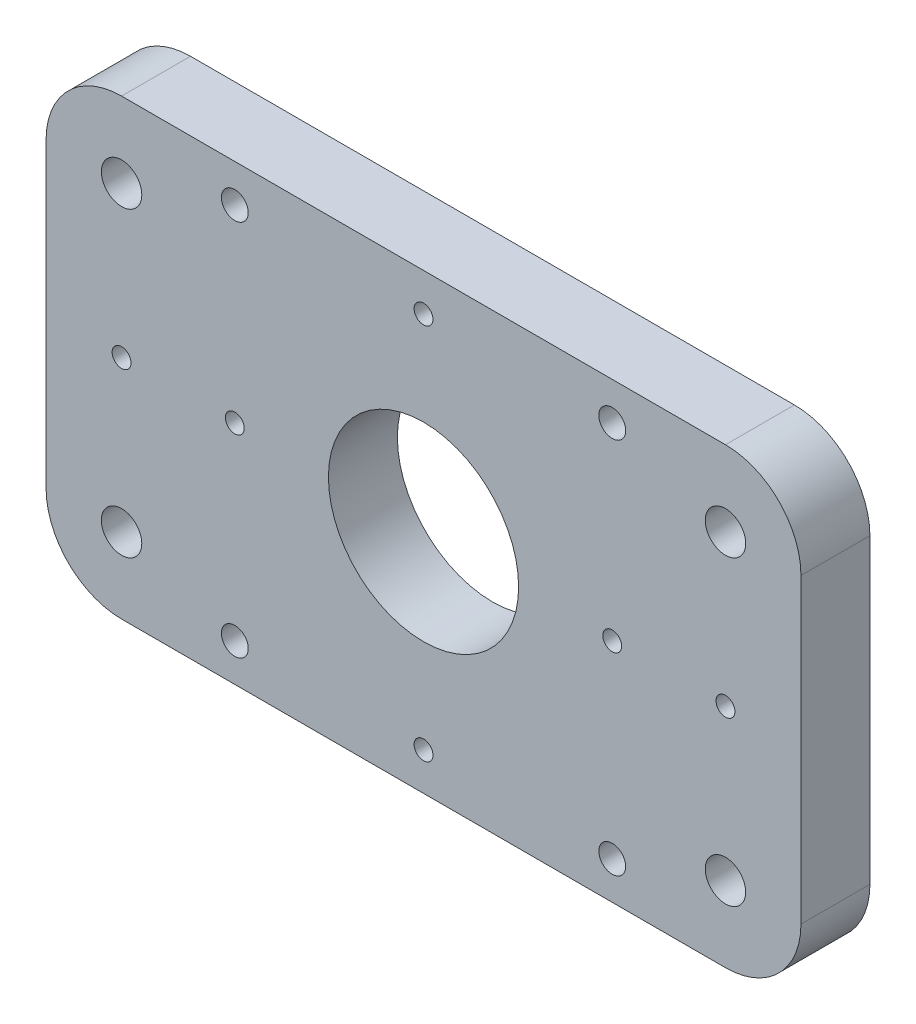
SolidWorks part; units mm, degrees
material "Balsa"
ref_plane "Front Plane" through (0, 0, 0) normal (0, 0, 1) x (1, 0, 0)
ref_plane "Top Plane" through (0, 0, 0) normal (0, 1, 0) x (1, 0, 0)
ref_plane "Right Plane" through (0, 0, 0) normal (1, 0, 0) x (0, 0, -1)
sketch "Sketch1" plane through (0, 0, 0) normal (0, 0, 1) x (1, 0, 0)
  line L1 (0, 0) -> (-38.1, 0)
  line L2 (0, 0) -> (0, 38.1)
  line L3 (0, 38.1) -> (-38.1, 38.1)
  line L4 (-38.1, 0) -> (-38.1, 38.1)
  dimension "D1" = 38.1
extrude "Boss-Extrude1" add sketch "Sketch1" along normal blind 5.8
sketch "Sketch2" plane through (0, 0, 5.8) normal (0, 0, 1) x (1, 0, 0)
  line L0 (-19.05, 19.05) -> (-38.1, 19.05) construction
  line L1 (-38.1, 38.1) -> (-38.1, 0) construction
  line L2 (-19.05, 19.05) -> (-19.05, 0) construction
  line L3 (-38.1, 0) -> (0, 0) construction
  circle A0 centre (-19.05, 19.05) radius 8
  dimension "D1" = 16
extrude "Cut-Extrude1" cut sketch "Sketch2" against normal blind 12.7
sketch "Sketch3" plane through (0, 0, 5.8) normal (0, 0, 1) x (1, 0, 0)
  line L0 (-38.1, 38.1) -> (0, 0) construction
  line L1 (0, 38.1) -> (-38.1, 0) construction
  line L2 (-34.925, 34.925) -> (-34.925, 3.175) construction
  line L3 (-34.925, 3.175) -> (-3.175, 3.175) construction
  line L4 (-3.175, 3.175) -> (-3.175, 34.925) construction
  line L5 (-3.175, 34.925) -> (-34.925, 34.925) construction
  line L6 (0, 38.1) -> (-38.1, 38.1) construction
  circle A0 centre (-34.925, 34.925) radius 1.13
  circle A1 centre (-3.175, 34.925) radius 1.13
  circle A2 centre (-3.175, 3.175) radius 1.13
  circle A3 centre (-34.925, 3.175) radius 1.13
  dimension "D2" = 2.26
  dimension "D1" = 3.175
extrude "Cut-Extrude2" cut sketch "Sketch3" against normal through all
sketch "Sketch4" plane through (0, 0, 5.8) normal (0, 0, 1) x (1, 0, 0)
  line L0 (-19.05, 38.1) -> (-19.05, 0) construction
  line L1 (0, 38.1) -> (-38.1, 38.1) construction
  line L2 (-38.1, 0) -> (0, 0) construction
  line L3 (-19.05, 19.05) -> (-38.1, 19.05) construction
  line L4 (-38.1, 38.1) -> (-38.1, 0) construction
  circle A0 centre (-34.925, 19.05) radius 0.7937
  circle A1 centre (-19.05, 34.925) radius 0.7937
  circle A2 centre (-3.175, 19.05) radius 0.7938
  circle A3 centre (-19.05, 3.175) radius 0.7937
  dimension "D2" = 1.5875
  dimension "D1" = 3.175
  dimension "D3" = 4
extrude "Cut-Extrude3" cut sketch "Sketch4" against normal through all
sketch "Sketch5" plane through (0, 0, 5.8) normal (0, 0, 1) x (1, 0, 0)
  line L0 (-38.1, 38.1) -> (-38.1, 0) construction
  line L1 (-38.1, 38.1) -> (-50.8, 38.1)
  line L2 (-38.1, 38.1) -> (-38.1, 0)
  line L3 (-38.1, 0) -> (-50.8, 0)
  line L4 (-50.8, 38.1) -> (-50.8, 0)
  line L5 (0, 38.1) -> (12.7, 38.1)
  line L6 (0, 38.1) -> (0, 0)
  line L7 (0, 0) -> (12.7, 0)
  line L8 (12.7, 38.1) -> (12.7, 0)
  line L9 (-38.1, 0) -> (0, 0) construction
  dimension "D1" = 12.7
extrude "Boss-Extrude2" add sketch "Sketch5" against normal through all
hole_wizard "M3 Clearance Hole1" positions "Sketch7" profile "Sketch6" hole size "M3" standard "Ansi Metric"
sketch "Sketch7" plane through (0, 0, 0) normal (0, 0, -1) x (-1, 0, 0)
  line L0 (-6.35, 38.1) -> (-6.35, 0) construction
  line L1 (-12.7, 38.1) -> (50.8, 38.1) construction
  line L2 (50.8, 0) -> (-12.7, 0) construction
  line L4 (19.05, 38.1) -> (19.05, 0) construction
  line L6 (-12.7, 0) -> (-12.7, 38.1) construction
  line L7 (-12.7, 31.75) -> (50.8, 31.75) construction
  line L8 (50.8, 38.1) -> (50.8, 0) construction
  line L10 (-12.7, 19.05) -> (50.8, 19.05) construction
  point P0 (-6.35, 31.75)
  point P30 (44.45, 31.75)
  point P32 (44.45, 6.35)
  point P33 (-6.35, 6.35)
  dimension "D1" = 6.35
  dimension "D2" = 6.35
sketch "Sketch6" plane through (6.35, 31.75, 0) normal (1, 0, 0) x (0, 1, 0)
  line L0 (0, 0) -> (0, 11.0215)
  line L1 (0, 11.0215) -> (1.7, 10)
  line L2 (1.7, 10) -> (1.7, 0)
  line L5 (1.7, 0) -> (0, 0)
  line L10 (0, 11.0215) -> (-1.7, 10) construction
  line L11 (0, -6.35) -> (0, 107.95) construction
  dimension "Hole Dia." = 3.4
  dimension "Hole Depth" = 10
  dimension "Drill Angle" = 118
sketch "Sketch9" plane through (0, 0, 0) normal (0, 0, -1) x (-1, 0, 0)
  line L0 (-6.35, 31.75) -> (-6.35, 6.35) construction
  line L1 (44.45, 31.75) -> (44.45, 6.35) construction
  circle A0 centre (-6.35, 19.05) radius 0.7938
  circle A1 centre (44.45, 19.05) radius 0.7937
  dimension "D1" = 1.5875
extrude "Cut-Extrude4" cut sketch "Sketch9" against normal through all
fillet "Fillet1" radius 6.35 4 edges at (-50.8, 0, 2.9) (-50.8, 38.1, 2.9) (12.7, 0, 2.9) (12.7, 38.1, 2.9)
